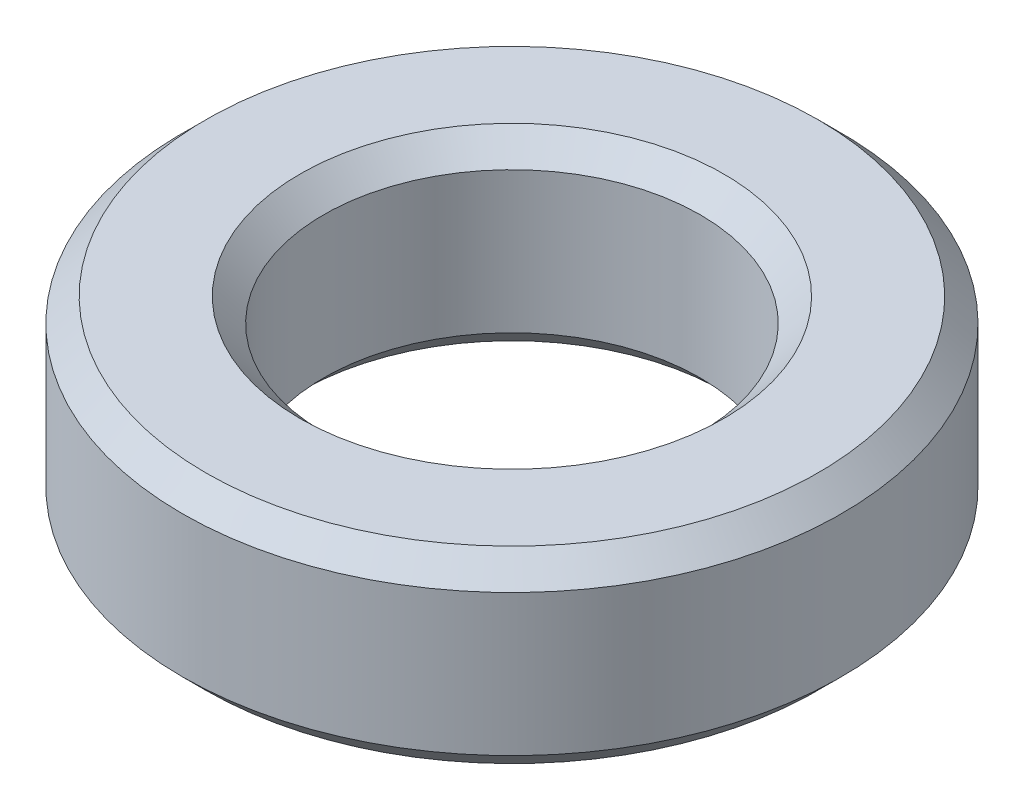
SolidWorks part; units mm, degrees
ref_plane "Front" through (0, 0, 0) normal (0, 0, 1) x (1, 0, 0)
ref_plane "Top" through (0, 0, 0) normal (0, 1, 0) x (1, 0, 0)
ref_plane "Right" through (0, 0, 0) normal (1, 0, 0) x (0, 0, -1)
sketch "Sketch1" plane through (0, 0, 0) normal (0, 1, 0) x (1, 0, 0)
  circle A0 centre (0, 0) radius 4
  circle A1 centre (0, 0) radius 7
extrude "Boss-Extrude1" add sketch "Sketch1" along normal blind 4
chamfer "Chamfer1" distance 0.5 angle 45 4 edges at (0, 0, 4) (0, 4, 4) (0, 4, 7) (0, 0, 7)
